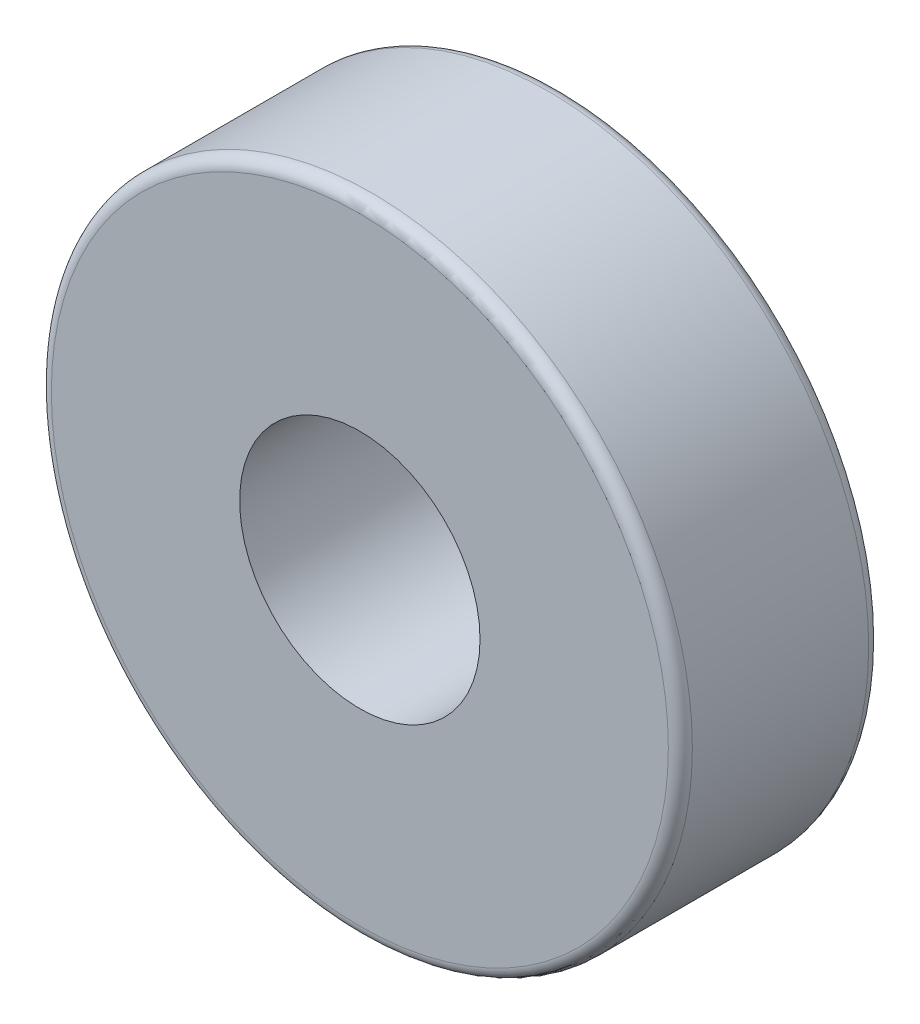
SolidWorks part; units mm, degrees
material "Plain Carbon Steel"
ref_plane "Front Plane" through (0, 0, 0) normal (0, 0, 1) x (1, 0, 0)
ref_plane "Top Plane" through (0, 0, 0) normal (0, 1, 0) x (1, 0, 0)
ref_plane "Right Plane" through (0, 0, 0) normal (1, 0, 0) x (0, 0, -1)
sketch "Sketch1" plane through (0, 0, 0) normal (0, 0, 1) x (1, 0, 0)
  circle A0 centre (0, 0) radius 8
  circle A1 centre (0, 0) radius 3
  dimension "D1" = 6
  dimension "D2" = 16
extrude "Boss-Extrude1" add sketch "Sketch1" along normal mid plane 5
fillet "Fillet2" radius 0.3 3 edges at (8, 0, 2.5) (8, 0, -2.5) (3, 0, -2.5)
